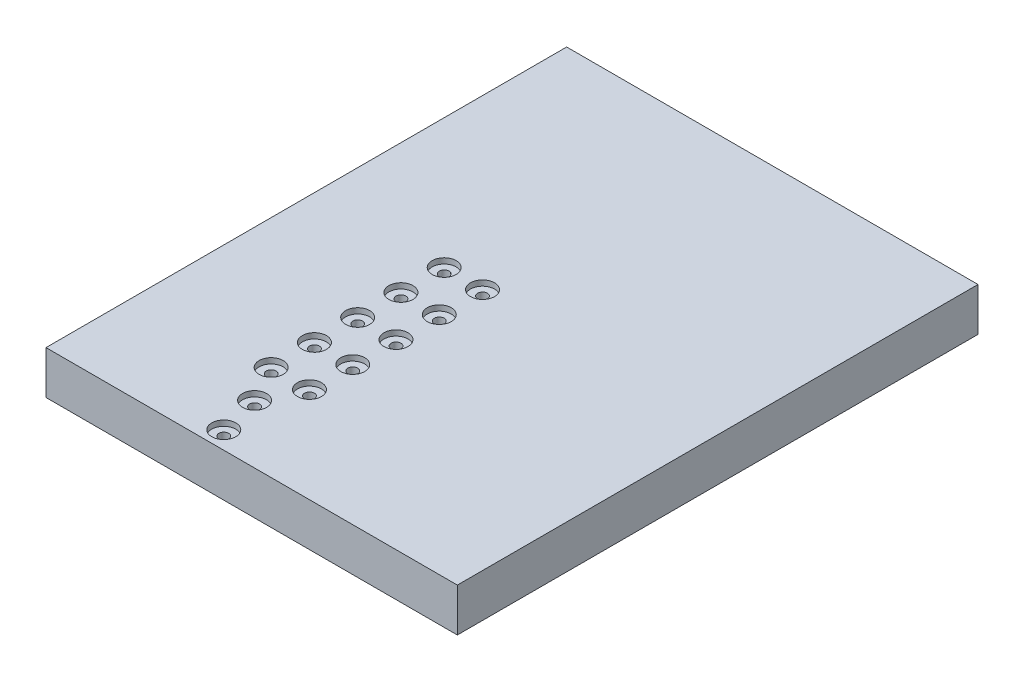
SolidWorks part; units mm, degrees
ref_plane "Front Plane" through (0, 0, 0) normal (0, 0, 1) x (1, 0, 0)
ref_plane "Top Plane" through (0, 0, 0) normal (0, 1, 0) x (1, 0, 0)
ref_plane "Right Plane" through (0, 0, 0) normal (1, 0, 0) x (0, 0, -1)
sketch "Sketch1" plane through (0, 0, 0) normal (0, 1, 0) x (1, 0, 0)
  line L1 (-34.43, 36.442) -> (60.6546, 36.442)
  line L2 (-34.43, 36.442) -> (-34.43, -83.9113)
  line L3 (-34.43, -83.9113) -> (60.6546, -83.9113)
  line L4 (60.6546, 36.442) -> (60.6546, -83.9113)
extrude "Boss-Extrude1" add sketch "Sketch1" along normal blind 10
hole_wizard "CBORE for #2 Binding Head Machine Screw1" positions "Sketch2" profile "Sketch3" counterbore size "#2" standard "ANSI Inch"
sketch "Sketch2" plane through (0, 10, 0) normal (0, 1, 0) x (1, 0, 0)
  line L0 (-34.43, 36.442) -> (-34.43, -83.9113) construction
  line L1 (-34.43, -83.9113) -> (60.6546, -83.9113) construction
  point P0 (-4.43, -61.8649)
  point P24 (0, 0)
  point P25 (0, 0)
  point P26 (0, 0)
  dimension "D1" = 30
  dimension "D2" = 22.0464
sketch "Sketch3" plane through (-4.43, 10, 61.8649) normal (1, 0, 0) x (0, 0, 1)
  line L0 (0, 0) -> (0, 3.6792)
  line L1 (0, 3.6792) -> (1.1303, 3)
  line L2 (1.1303, 3) -> (1.1303, 1.27)
  line L3 (1.1303, 1.27) -> (2.7788, 1.27)
  line L4 (2.7788, 1.27) -> (2.7788, 0)
  line L5 (2.7788, 0) -> (0, 0)
  line L10 (0, 3.6792) -> (-1.1303, 3) construction
  line L11 (0, -6.35) -> (0, 107.95) construction
  dimension "Hole Dia." = 2.2606
  dimension "Hole Depth" = 3
  dimension "C'Bore Dia." = 5.5575
  dimension "C'Bore Depth" = 1.27
  dimension "Drill Angle" = 118
pattern_linear "LPattern1" count 5 spacing 10 along (0, 0, -1) of "CBORE for #2 Binding Head Machine Screw1"
pattern_circular "CirPattern1" count 5 over 60 about axis through (-34.43, 0, 83.9113) along (0, 1, 0) skipping 3, 4 of "CBORE for #2 Binding Head Machine Screw1"
mirror "Mirror1" about plane through (0, 0, 0) normal (1, 0, 0) of "LPattern1", "CBORE for #2 Binding Head Machine Screw1"
